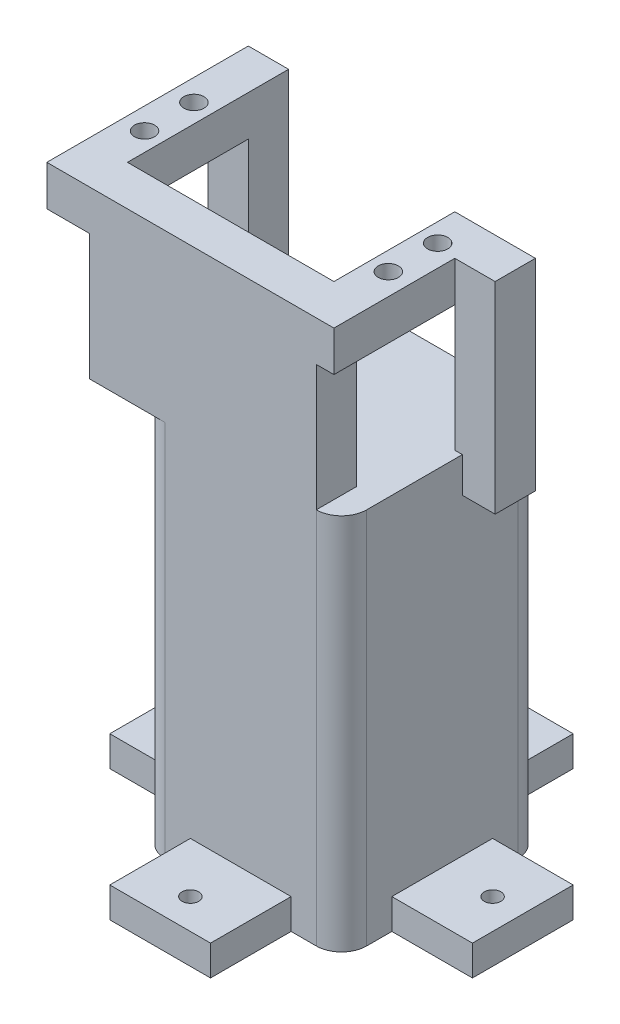
SolidWorks part; units mm, degrees
ref_plane "前视基准面" through (0, 0, 0) normal (0, 0, 1) x (1, 0, 0)
ref_plane "上视基准面" through (0, 0, 0) normal (0, 1, 0) x (1, 0, 0)
ref_plane "右视基准面" through (0, 0, 0) normal (1, 0, 0) x (0, 0, -1)
other "Configuration Table"
sketch "草图1" plane through (0, 0, 0) normal (0, 1, 0) x (1, 0, 0)
  line L0 (0, 40.8862) -> (0, 0) construction
  line L5 (0, 0) -> (-31.165, 31.165) construction
  line L6 (0, 0) -> (33.4198, 33.4198) construction
  line L7 (-10, 36) -> (-10, 10)
  line L8 (-10, 36) -> (10, 36)
  line L9 (10, 36) -> (10, 10)
  line L10 (36, -10) -> (10, -10)
  line L11 (36, 10) -> (10, 10)
  line L12 (36, 10) -> (36, -10)
  line L13 (40.8862, 0) -> (0, 0) construction
  line L14 (-10, -36) -> (-10, -10)
  line L15 (10, -36) -> (10, -10)
  line L16 (10, -36) -> (-10, -36)
  line L17 (0, -40.8862) -> (0, 0) construction
  line L18 (-36, 10) -> (-10, 10)
  line L19 (-36, -10) -> (-10, -10)
  line L20 (-36, -10) -> (-36, 10)
  line L21 (-40.8862, 0) -> (0, 0) construction
  circle A4 centre (0, 30) radius 1.65
  circle A5 centre (30, 0) radius 1.65
  circle A6 centre (0, -30) radius 1.65
  circle A7 centre (-30, 0) radius 1.65
  point P5 (0, 0)
  point P8 (0, 0)
  point P12 (0, 36)
  point P13 (-55.7159, 17.2502)
  point P16 (-50.8866, 17.1153)
  point P36 (0, 0)
  dimension "D4" = 20
  dimension "D6" = 3.3
  dimension "D1" = 45
  dimension "D2" = 45
  dimension "D3" = 30
  dimension "D5" = 36
  dimension "D7" = 4
extrude "凸台-拉伸1" add sketch "草图1" along normal blind 6
sketch "草图2" plane through (0, 0, 0) normal (0, 1, 0) x (1, 0, 0)
  line L1 (-15, 20) -> (15, 20)
  line L2 (-20, 15) -> (-20, -15)
  line L3 (-15, -20) -> (15, -20)
  line L4 (20, 15) -> (20, -15)
  line L5 (-20, 20) -> (20, -20) construction
  line L6 (-20, -20) -> (20, 20) construction
  arc A0 (-20, 15) -> (-15, 20) centre (-15, 15) cw
  arc A1 (-20, -15) -> (-15, -20) centre (-15, -15) ccw
  arc A2 (15, -20) -> (20, -15) centre (15, -15) ccw
  arc A3 (20, 15) -> (15, 20) centre (15, 15) ccw
  point P0 (0, 0)
  dimension "D3" = 5
  dimension "D4" = 5
  dimension "D1" = 40
  dimension "D2" = 40
extrude "凸台-拉伸2" add sketch "草图2" along normal blind 75
sketch "草图3" plane through (0, 75, 0) normal (0, 1, 0) x (1, 0, 0)
  line L0 (-10, -20) -> (-10, 12) construction
  line L1 (-38.5, -20) -> (18.5, -20)
  line L2 (-38.5, -20) -> (-38.5, 12)
  line L3 (-38.5, 12) -> (-30.5, 12)
  line L4 (18.5, -20) -> (18.5, 12)
  line L6 (-30.5, -12) -> (10.5, -12)
  line L7 (-30.5, -12) -> (-30.5, 12)
  line L9 (10.5, -12) -> (10.5, 12)
  line L10 (-30.5, -12) -> (10.5, 12) construction
  line L11 (-30.5, 12) -> (10.5, -12) construction
  line L12 (-30, 10) -> (-34.5, 10) construction
  line L13 (10.5, 12) -> (18.5, 12)
  circle A0 centre (-34.2, -4.9) radius 2
  circle A1 centre (-34.2, 4.9) radius 2
  circle A2 centre (14.2, -4.9) radius 2
  circle A3 centre (14.2, 4.9) radius 2
  point P6 (-10, 0)
  point P25 (-10, -12)
  dimension "D1" = 4
  dimension "D2" = 4
  dimension "D3" = 4
  dimension "D4" = 4
  dimension "D5" = 8
  dimension "D6" = 2
  dimension "D7" = 41
  dimension "D8" = 8
  dimension "D9" = 12
extrude "凸台-拉伸3" add sketch "草图3" against normal blind 8 from surface separate body
sketch "草图5" plane through (0, 75, 0) normal (0, 1, 0) x (1, 0, 0)
  line L1 (15, -20) -> (-30, -20)
  line L2 (15, -20) -> (15, -12)
  line L3 (15, -12) -> (-30, -12)
  line L4 (-30, -20) -> (-30, -12)
  dimension "D1" = 8
  dimension "D2" = 45
extrude "凸台-拉伸4" add sketch "草图5" along normal up to next
sketch "草图6" plane through (0, 75, 0) normal (0, 1, 0) x (1, 0, 0)
  line L1 (18.5, 12) -> (26.5, 12)
  line L2 (18.5, 12) -> (18.5, 4)
  line L3 (18.5, 4) -> (26.5, 4)
  line L4 (26.5, 12) -> (26.5, 4)
  dimension "D1" = 8
  dimension "D2" = 8
extrude "凸台-拉伸5" add sketch "草图6" against normal blind 40 from surface at 33 starting at face at (14.2, 108, 2.9)
sketch "草图7" plane through (0, 108, 0) normal (0, 1, 0) x (1, 0, 0)
  line L0 (-38.5, 12) -> (-38.5, -20) construction
  line L1 (-30.5, 12) -> (-38.5, 12)
  line L2 (-30.5, 12) -> (-30.5, 20)
  line L3 (-30.5, 20) -> (-38.5, 20)
  line L4 (-38.5, 12) -> (-38.5, 20)
  dimension "D1" = 8
extrude "凸台-拉伸6" add sketch "草图7" against normal blind 50
sketch "草图8" plane through (-38.5, 0, 0) normal (-1, 0, 0) x (0, 0, 1)
  line L1 (-20, 58) -> (-12, 58)
  line L2 (-20, 58) -> (-20, 75)
  line L3 (-20, 75) -> (-12, 75)
  line L4 (-12, 58) -> (-12, 75)
extrude "凸台-拉伸7" add sketch "草图8" against normal blind 40
